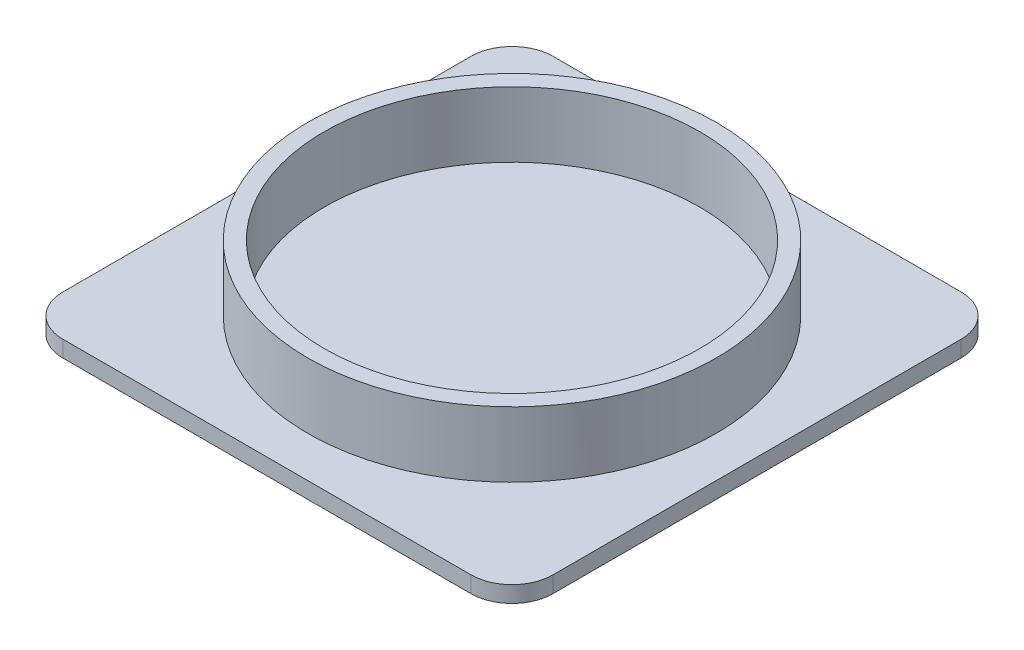
SolidWorks part; units mm, degrees
ref_plane "Front Plane" through (0, 0, 0) normal (0, 0, 1) x (1, 0, 0)
ref_plane "Top Plane" through (0, 0, 0) normal (0, 1, 0) x (1, 0, 0)
ref_plane "Right Plane" through (0, 0, 0) normal (1, 0, 0) x (0, 0, -1)
sketch "Sketch1" plane through (0, 0, 0) normal (0, 1, 0) x (1, 0, 0)
  circle A0 centre (0, 0) radius 31.75
  circle A1 centre (0, 0) radius 29.21
  dimension "D1" = 63.5
  dimension "D2" = 2.54
extrude "Boss-Extrude1" add sketch "Sketch1" along normal blind 12.7
sketch "Sketch2" plane through (0, 0, 0) normal (0, 1, 0) x (1, 0, 0)
  line L1 (-38.1, -38.1) -> (38.1, -38.1)
  line L2 (-38.1, -38.1) -> (-38.1, 38.1)
  line L3 (-38.1, 38.1) -> (38.1, 38.1)
  line L4 (38.1, -38.1) -> (38.1, 38.1)
  line L5 (-38.1, -38.1) -> (38.1, 38.1) construction
  line L6 (-38.1, 38.1) -> (38.1, -38.1) construction
  point P0 (0, 0)
  dimension "D1" = 76.2
extrude "Boss-Extrude2" add sketch "Sketch2" along normal blind 2.54
fillet "Fillet1" radius 6.35 4 edges at (-38.1, 1.27, -38.1) (-38.1, 1.27, 38.1) (38.1, 1.27, -38.1) (38.1, 1.27, 38.1)
